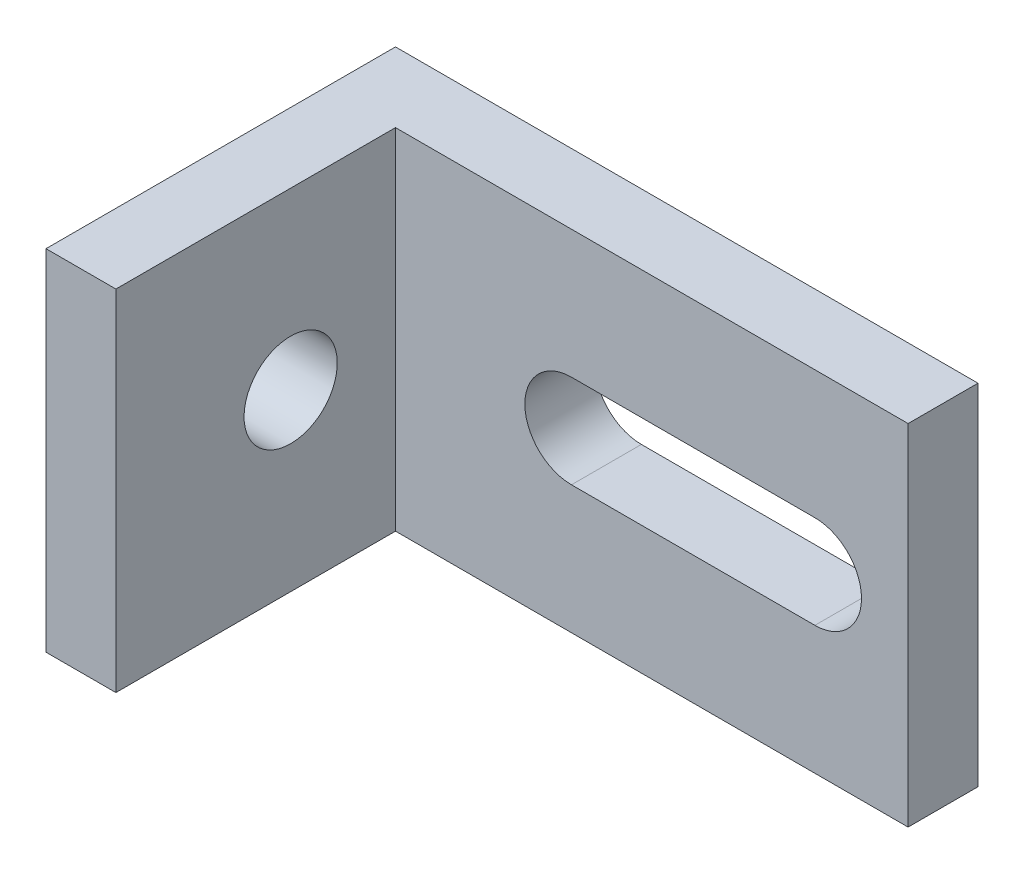
SolidWorks part; units mm, degrees
ref_plane "Front Plane" through (0, 0, 0) normal (0, 0, 1) x (1, 0, 0)
ref_plane "Top Plane" through (0, 0, 0) normal (0, 1, 0) x (1, 0, 0)
ref_plane "Right Plane" through (0, 0, 0) normal (1, 0, 0) x (0, 0, -1)
sketch "Sketch1" plane through (0, 0, 0) normal (0, 0, 1) x (1, 0, 0)
  line L1 (-12.5, 7.5) -> (12.5, 7.5)
  line L2 (-12.5, 7.5) -> (-12.5, -7.5)
  line L3 (-12.5, -7.5) -> (12.5, -7.5)
  line L4 (12.5, 7.5) -> (12.5, -7.5)
  line L5 (-12.5, 7.5) -> (12.5, -7.5) construction
  line L6 (-12.5, -7.5) -> (12.5, 7.5) construction
  point P0 (0, 0)
  dimension "D1" = 15
  dimension "D2" = 25
extrude "Boss-Extrude1" add sketch "Sketch1" along normal blind 3
sketch "Sketch2" plane through (0, 0, 3) normal (0, 0, 1) x (1, 0, 0)
  line L0 (8.5, 0) -> (-1.9474, 0) construction
  line L1 (8.5, -2) -> (-1.9474, -2)
  line L2 (8.5, 2) -> (-1.9474, 2)
  line L3 (12.5, -7.5) -> (12.5, 7.5) construction
  arc A0 (8.5, -2) -> (8.5, 2) centre (8.5, 0) ccw
  arc A1 (-1.9474, 2) -> (-1.9474, -2) centre (-1.9474, 0) ccw
  point P3 (3.2763, 0)
  dimension "D1" = 2
  dimension "D2" = 4
extrude "Cut-Extrude1" cut sketch "Sketch2" against normal blind 3
sketch "Sketch3" plane through (0, 0, 3) normal (0, 0, 1) x (1, 0, 0)
  line L0 (-12.5, -7.5) -> (12.5, -7.5) construction
  line L1 (-12.5, 7.5) -> (-9.5, 7.5)
  line L2 (-12.5, 7.5) -> (-12.5, -7.5)
  line L3 (-12.5, -7.5) -> (-9.5, -7.5)
  line L4 (-9.5, 7.5) -> (-9.5, -7.5)
  dimension "D1" = 3
extrude "Boss-Extrude2" add sketch "Sketch3" along normal blind 12
sketch "Sketch4" plane through (-12.5, 0, 0) normal (-1, 0, 0) x (0, 0, 1)
  circle A0 centre (7.5, 0) radius 2
  dimension "D1" = 4
  dimension "D2" = 7.5
extrude "Cut-Extrude2" cut sketch "Sketch4" against normal blind 12
